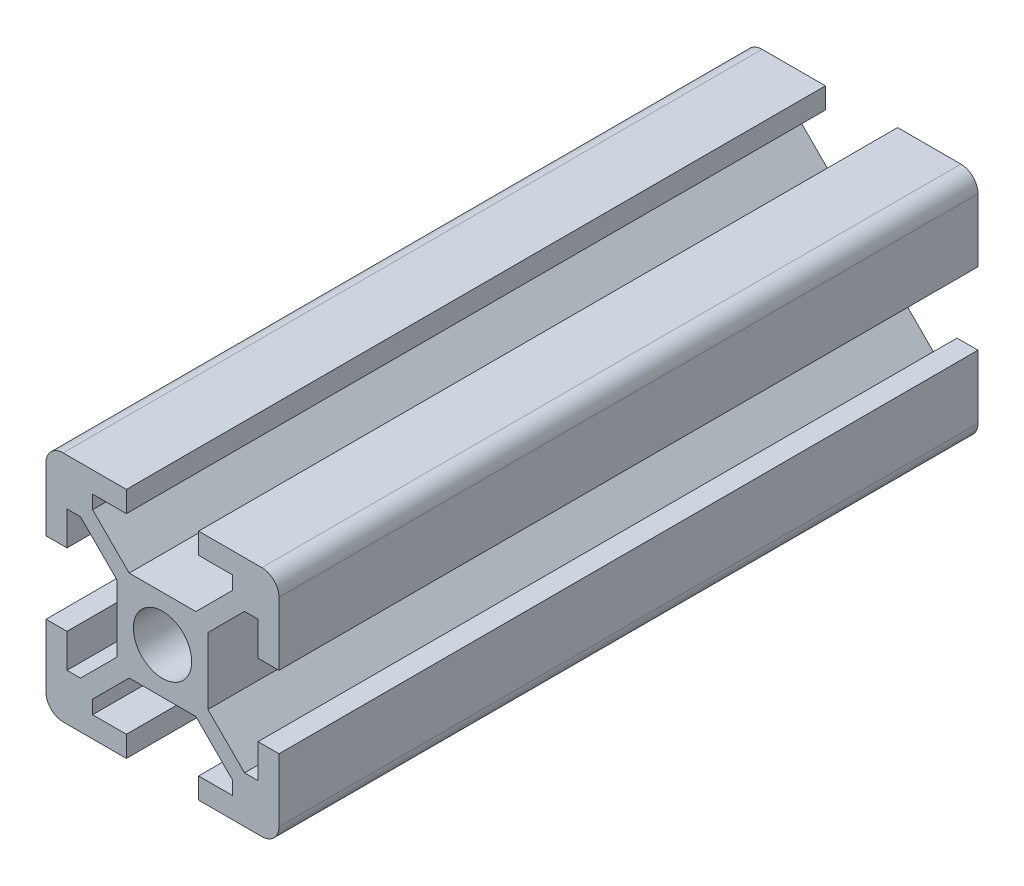
SolidWorks part; units mm, degrees
ref_plane "Front Plane" through (0, 0, 0) normal (0, 0, 1) x (1, 0, 0)
ref_plane "Top Plane" through (0, 0, 0) normal (0, 1, 0) x (1, 0, 0)
ref_plane "Right Plane" through (0, 0, 0) normal (1, 0, 0) x (0, 0, -1)
sketch "Sketch1" plane through (0, 0, 0) normal (0, 0, 1) x (1, 0, 0)
  line L0 (2.8606, 3.9) -> (6, 7.0394)
  line L5 (0, 3.9) -> (2.8606, 3.9)
  line L8 (3.9, 2.8606) -> (3.9, 0)
  line L9 (3.9, 0) -> (3.9, -2.8606)
  line L10 (3.9, -2.8606) -> (7.0394, -6)
  line L11 (6, 7.0394) -> (6, 8.2)
  line L12 (6, 8.2) -> (3.1, 8.2)
  line L13 (3.1, 8.2) -> (3.1, 10)
  line L14 (3.1, 10) -> (10, 10)
  line L15 (10, 10) -> (10, 3.1)
  line L16 (10, 3.1) -> (8.2, 3.1)
  line L17 (8.2, 3.1) -> (8.2, 6)
  line L18 (8.2, 6) -> (7.0394, 6)
  line L19 (7.0394, 6) -> (3.9, 2.8606)
  line L22 (7.0394, -6) -> (8.2, -6)
  line L23 (8.2, -6) -> (8.2, -3.1)
  line L24 (8.2, -3.1) -> (10, -3.1)
  line L25 (10, -3.1) -> (10, -10)
  line L26 (10, -10) -> (3.1, -10)
  line L27 (3.1, -10) -> (3.1, -8.2)
  line L28 (3.1, -8.2) -> (6, -8.2)
  line L29 (6, -8.2) -> (6, -7.0394)
  line L30 (6, -7.0394) -> (2.8606, -3.9)
  line L31 (2.8606, -3.9) -> (0, -3.9)
  line L32 (0, -3.9) -> (-2.8606, -3.9)
  line L33 (-2.8606, -3.9) -> (-6, -7.0394)
  line L34 (-6, -7.0394) -> (-6, -8.2)
  line L35 (-6, -8.2) -> (-3.1, -8.2)
  line L36 (-3.1, -8.2) -> (-3.1, -10)
  line L37 (-3.1, -10) -> (-10, -10)
  line L38 (-10, -10) -> (-10, -3.1)
  line L39 (-10, -3.1) -> (-8.2, -3.1)
  line L40 (-8.2, -3.1) -> (-8.2, -6)
  line L41 (-8.2, -6) -> (-7.0394, -6)
  line L42 (-7.0394, -6) -> (-3.9, -2.8606)
  line L43 (-3.9, -2.8606) -> (-3.9, 0)
  line L44 (-3.9, 0) -> (-3.9, 2.8606)
  line L45 (-3.9, 2.8606) -> (-7.0394, 6)
  line L46 (-7.0394, 6) -> (-8.2, 6)
  line L47 (-8.2, 6) -> (-8.2, 3.1)
  line L48 (-8.2, 3.1) -> (-10, 3.1)
  line L49 (-10, 3.1) -> (-10, 10)
  line L50 (-10, 10) -> (-3.1, 10)
  line L51 (-3.1, 10) -> (-3.1, 8.2)
  line L52 (-3.1, 8.2) -> (-6, 8.2)
  line L53 (-6, 8.2) -> (-6, 7.0394)
  line L54 (-6, 7.0394) -> (-2.8606, 3.9)
  line L55 (-2.8606, 3.9) -> (0, 3.9)
  circle A0 centre (0, 0) radius 2.5
  point P0 (0, 0)
  dimension "D9" = 5
  dimension "D1" = 45
  dimension "D2" = 10
  dimension "D3" = 6.1
  dimension "D4" = 3.1
  dimension "D5" = 1.47
  dimension "D6" = 4.3
  dimension "D7" = 6
  dimension "D8" = 4
extrude "Boss-Extrude1" add sketch "Sketch1" along normal blind 60
fillet "Fillet1" radius 1.47 4 edges at (-10, -10, 30) (-10, 10, 30) (10, -10, 30) (10, 10, 30)
sketch "Sketch2" plane through (3.9, 0, 0) normal (1, 0, 0) x (0, 0, -1)
  line L0 (-60, -2.8606) -> (-60, 2.8606) construction
  circle A0 centre (-50, 0) radius 1.5
  circle A1 centre (-40, 0) radius 1.5
  circle A2 centre (-30, 0) radius 1.5
  circle A3 centre (-20, 0) radius 1.5
  dimension "D1" = 3
  dimension "D2" = 10
  dimension "D3" = 4
extrude "Cut-Extrude1" cut sketch "Sketch2" against normal through all
